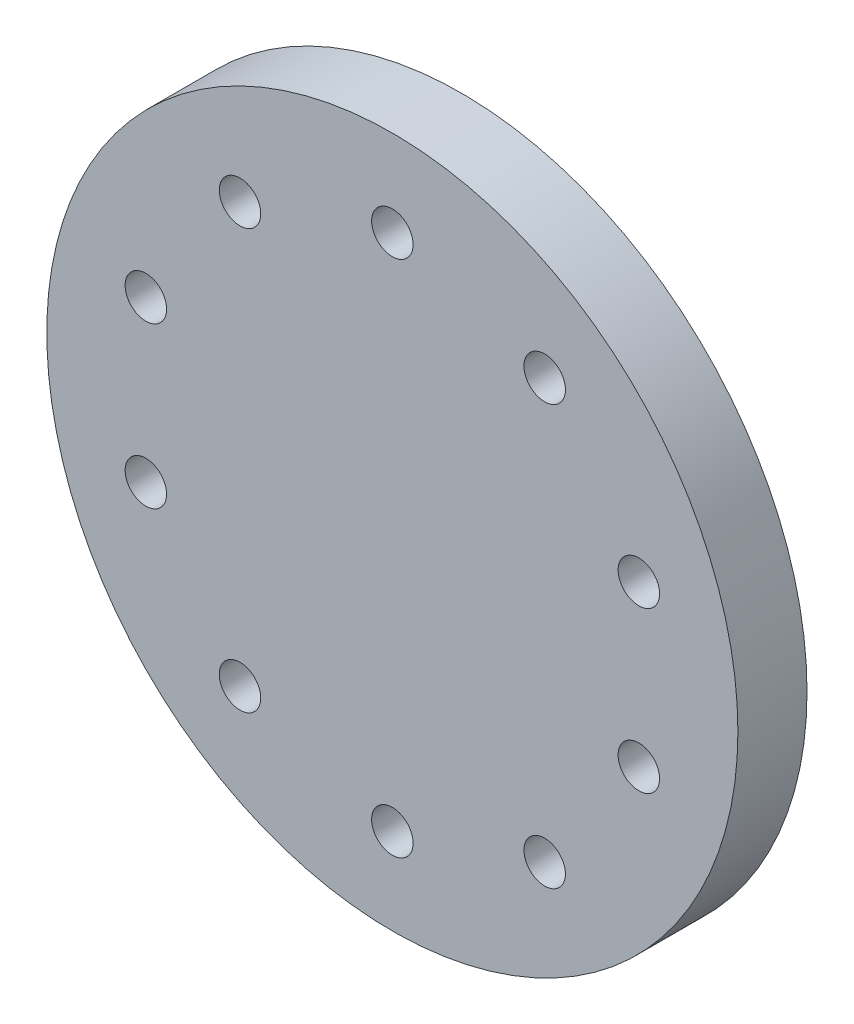
SolidWorks part; units mm, degrees
ref_plane "前基準面" through (0, 0, 0) normal (0, 0, 1) x (1, 0, 0)
ref_plane "上基準面" through (0, 0, 0) normal (0, 1, 0) x (1, 0, 0)
ref_plane "右基準面" through (0, 0, 0) normal (1, 0, 0) x (0, 0, -1)
sketch "草圖1" plane through (0, 0, 0) normal (0, 0, 1) x (1, 0, 0)
  circle A0 centre (0, 0) radius 10
  circle A1 centre (4.4084, 6.0676) radius 0.6
  circle A2 centre (0, 7.5) radius 0.6
  circle A3 centre (7.1329, 2.3176) radius 0.6
  circle A4 centre (7.1329, -2.3176) radius 0.6
  circle A5 centre (4.4084, -6.0676) radius 0.6
  circle A6 centre (0, -7.5) radius 0.6
  circle A7 centre (-4.4084, -6.0676) radius 0.6
  circle A8 centre (-7.1329, -2.3176) radius 0.6
  circle A9 centre (-7.1329, 2.3176) radius 0.6
  circle A10 centre (-4.4084, 6.0676) radius 0.6
  point P26 (0, 0)
  dimension "D1" = 10
  dimension "D2" = 20
  dimension "D3" = 1.2
extrude "填料-伸長1" add sketch "草圖1" along normal blind 2
sketch "草圖2" plane through (0, 0, 0) normal (0, 0, -1) x (-1, 0, 0)
  circle A0 centre (0, 0) radius 1.5
  dimension "D1" = 3
extrude "填料-伸長2" add sketch "草圖2" along normal blind 3
